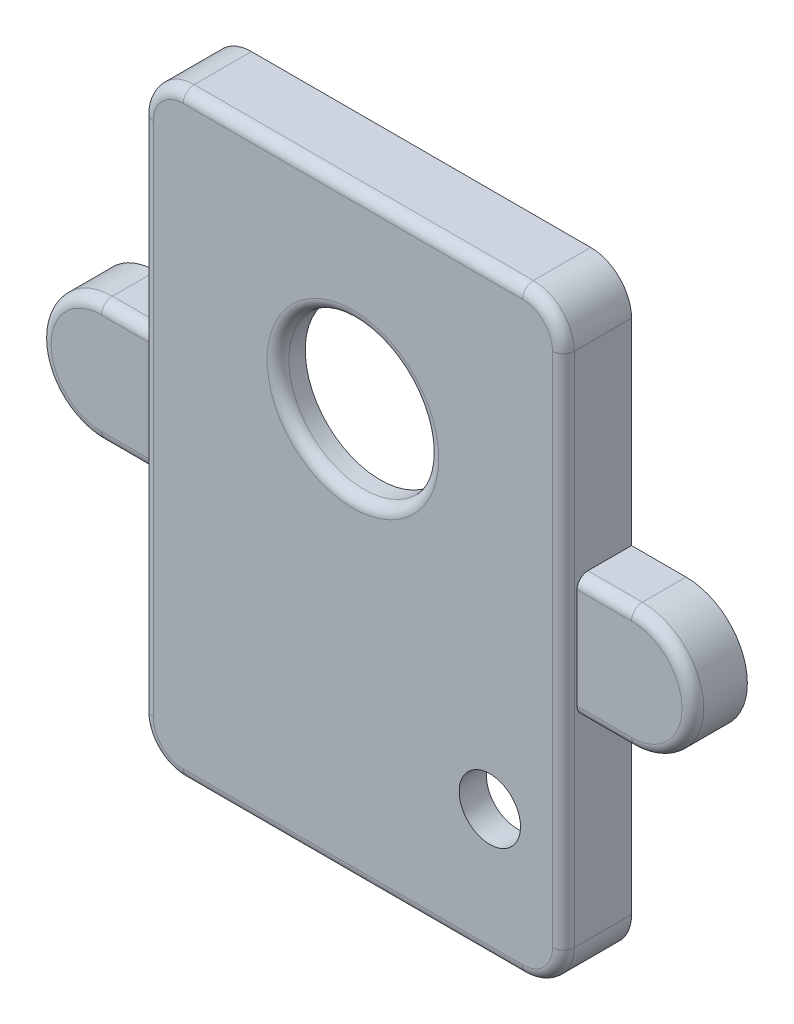
SolidWorks part; units mm, degrees
ref_plane "Front Plane" through (0, 0, 0) normal (0, 0, 1) x (1, 0, 0)
ref_plane "Top Plane" through (0, 0, 0) normal (0, 1, 0) x (1, 0, 0)
ref_plane "Right Plane" through (0, 0, 0) normal (1, 0, 0) x (0, 0, -1)
sketch "Sketch1" plane through (0, 0, 0) normal (0, 0, 1) x (1, 0, 0)
  line L1 (0, 0) -> (30.9, 0)
  line L2 (0, 0) -> (0, 43.9)
  line L3 (0, 43.9) -> (30.9, 43.9)
  line L4 (30.9, 0) -> (30.9, 43.9)
  line L5 (2, 41.9) -> (28.9, 41.9)
  line L6 (2, 41.9) -> (2, 2)
  line L7 (2, 2) -> (28.9, 2)
  line L8 (28.9, 41.9) -> (28.9, 2)
  dimension "D1" = 30.9
  dimension "D2" = 43.9
  dimension "D3" = 2
  dimension "D4" = 2
  dimension "D5" = 2
  dimension "D6" = 2
extrude "Boss-Extrude1" add sketch "Sketch1" along normal blind 5 contours L1 L4 L3 L2 L5 L8 L7 L6
sketch "Sketch2" plane through (0, 0, 5) normal (0, 0, 1) x (1, 0, 0)
  line L0 (0, 0) -> (30.9, 0) construction
  line L1 (0, 43.9) -> (30.9, 43.9)
  line L2 (0, 43.9) -> (0, 0)
  line L3 (0, 0) -> (30.9, 0)
  line L4 (30.9, 43.9) -> (30.9, 0)
  line L5 (30.9, 0) -> (30.9, 43.9) construction
extrude "Boss-Extrude2" add sketch "Sketch2" against normal blind 2
sketch "Sketch3" plane through (0, 0, 0) normal (0, 0, -1) x (-1, 0, 0)
  line L0 (-44.2299, 21.95) -> (-30.4, 21.95) construction
  line L3 (0, 0) -> (-30.9, 0) construction
  line L4 (-34.9, 26.45) -> (-30.9, 26.45)
  line L5 (-30.9, 0) -> (-30.9, 43.9) construction
  line L6 (-34.9, 17.45) -> (-30.9, 17.45)
  line L7 (-30.9, 26.45) -> (-30.9, 17.45)
  arc A0 (-34.9, 26.45) -> (-34.9, 17.45) centre (-34.9, 21.95) ccw
  dimension "D2" = 4
  dimension "D1" = 21.95
  dimension "D3" = 4
extrude "Boss-Extrude3" add sketch "Sketch3" against normal blind 4
sketch "Sketch4" plane through (0, 0, 0) normal (0, 0, -1) x (-1, 0, 0)
  circle A0 centre (-34.9, 21.95) radius 4
extrude "Cut-Extrude1" cut sketch "Sketch4" against normal blind 2
ref_plane "Plane1" through (15.45, 0, 0) normal (1, 0, 0) x (0, 0, -1)
mirror "Mirror1" about plane through (15.45, 0, 0) normal (1, 0, 0) of "Cut-Extrude1", "Boss-Extrude3"
sketch "Sketch5" plane through (0, 0, 5) normal (0, 0, 1) x (1, 0, 0)
  line L0 (15.45, 87.8) -> (15.45, 0)
  line L2 (0, 0) -> (30.9, 0) construction
  line L3 (0, 43.9) -> (30.9, 43.9) construction
  circle A0 centre (15.45, 29.9) radius 5.5
  point P3 (15.45, 43.9)
  dimension "D1" = 14
extrude "Cut-Extrude2" cut sketch "Sketch5" against normal through all contours L0 A0 | L0 A0
fillet "Fillet1" radius 3 4 edges at (30.9, 0, 2.5) (0, 0, 2.5) (30.9, 43.9, 2.5) (0, 43.9, 2.5)
fillet "Fillet2" radius 0.8 15 edges at (-2, 26.45, 4) (-2, 17.45, 4) (32.9, 26.45, 4) (32.9, 17.45, 4) (30.0213, 0.8787, 5) (15.45, 0, 5) (0.8787, 0.8787, 5) (0, 21.95, 5) (0.8787, 43.0213, 5) (15.45, 43.9, 5) (30.0213, 43.0213, 5) (20.95, 29.9, 5) (-8.5, 21.95, 4) (39.4, 21.95, 4) (30.9, 21.95, 5)
sketch "Sketch6" plane through (0, 0, 5) normal (0, 0, 1) x (1, 0, 0)
  line L0 (30.9, 40.9) -> (30.9, 3) construction
  line L1 (27.9, 0) -> (3, 0) construction
  circle A0 centre (25.5, 9.5) radius 2.25
  dimension "D1" = 5.4
  dimension "D2" = 9.5
extrude "Cut-Extrude3" cut sketch "Sketch6" against normal through all
